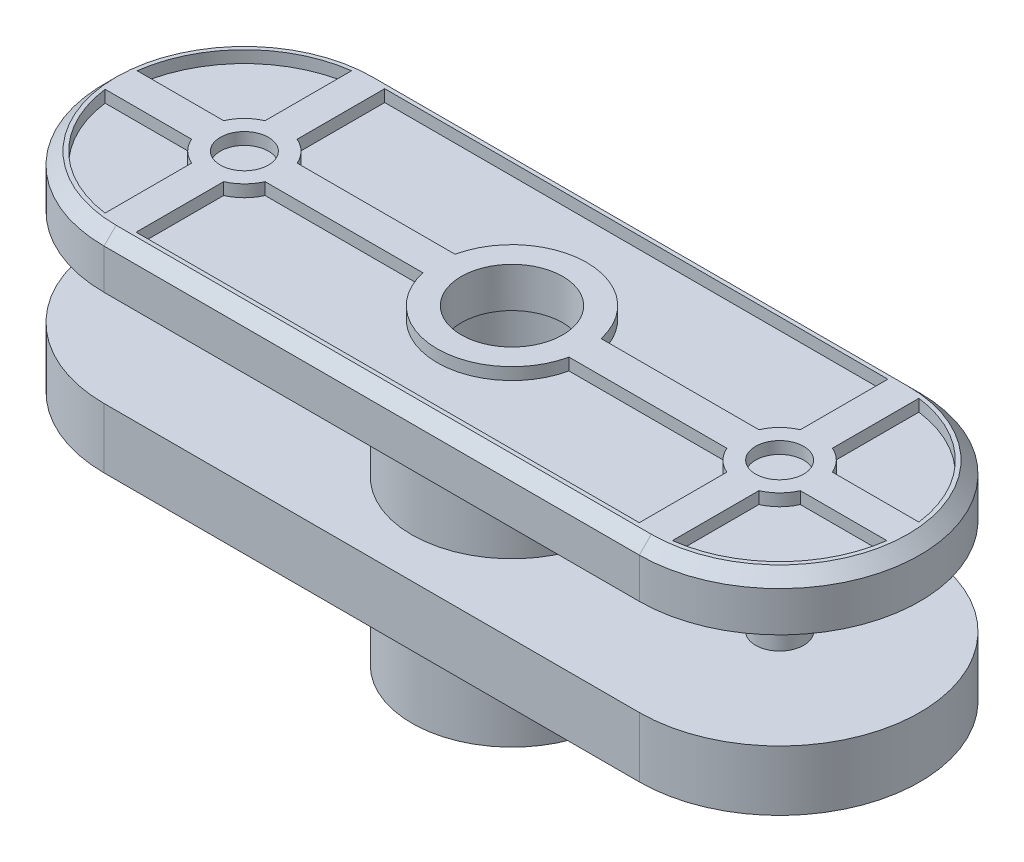
SolidWorks part; units mm, degrees
other "Marca1"
sketch "Croquis13" plane through (-10.175, 1.3, 3.5) normal (-0.1147, 0.8276, 0.5494) x (0.861, 0.3586, -0.3605)
ref_plane "Alzado" through (0, 0, 0) normal (0, 0, 1) x (1, 0, 0)
ref_plane "Planta" through (0, 0, 0) normal (0, 1, 0) x (1, 0, 0)
ref_plane "Vista lateral" through (0, 0, 0) normal (1, 0, 0) x (0, 0, -1)
sketch "Croquis1" plane through (0, 0, 0) normal (0, 1, 0) x (1, 0, 0)
  line L0 (-6.675, 0) -> (6.675, 0) construction
  line L1 (-6.675, 3.5) -> (6.675, 3.5)
  line L2 (6.675, -3.5) -> (-6.675, -3.5)
  line L3 (0, 6.0842) -> (0, -6.0842) construction
  arc A0 (6.675, 3.5) -> (6.675, -3.5) centre (6.675, 0) cw
  arc A1 (-6.675, 3.5) -> (-6.675, -3.5) centre (-6.675, 0) ccw
  point P0 (-10.175, 0)
  point P3 (0, -3.5)
  point P4 (0, 0)
  point P10 (0, 3.5)
  point P11 (10.175, 0)
  point P18 (0, 0)
  dimension "D1" = 20.35
  dimension "D2" = 7
extrude "Saliente-Extruir1" add sketch "Croquis1" along normal blind 1.3
sketch "Croquis2" plane through (0, 1.3, 0) normal (0, 1, 0) x (1, 0, 0)
  line L0 (-6.675, 3.5) -> (-6.675, -3.5) construction
  line L1 (-6.675, 0) -> (-10.175, 0) construction
  line L2 (-7.075, 3.0741) -> (-7.075, 0.9165)
  line L4 (-6.275, 3.1) -> (-6.275, 0.9165)
  line L6 (6.675, -3.5) -> (-6.675, -3.5) construction
  line L7 (-6.675, 3.5) -> (6.675, 3.5) construction
  line L8 (6.675, -3.5) -> (-6.675, -3.5)
  line L9 (-6.675, 3.5) -> (6.675, 3.5)
  line L10 (-7.075, 3.5) -> (-7.075, -3.5) construction
  line L11 (-6.275, -0.9165) -> (-6.275, -3.1)
  line L12 (-6.275, 3.5) -> (-6.275, -3.5) construction
  line L15 (-7.5915, -0.4) -> (-9.7491, -0.4)
  line L16 (-7.5915, 0.4) -> (-9.7491, 0.4)
  line L18 (-7.075, -0.9165) -> (-7.075, -3.0741)
  line L20 (-6.675, 0) -> (6.675, 0) construction
  line L21 (-6.675, 0) -> (6.675, 0) construction
  line L22 (0, 6.0842) -> (0, -6.0842) construction
  line L23 (-5.7585, 0.4) -> (5.7585, 0.4)
  line L24 (0, 0.4) -> (0, 0)
  line L25 (0, 6.0842) -> (0, -6.0842) construction
  line L26 (-6.675, 0.4) -> (6.675, 0.4) construction
  line L27 (6.275, -0.9165) -> (6.275, -3.1)
  line L28 (-5.7585, -0.4) -> (5.7585, -0.4)
  line L29 (7.075, -0.9165) -> (7.075, -3.0741)
  line L30 (7.5915, -0.4) -> (9.7491, -0.4)
  line L31 (7.5915, 0.4) -> (9.7491, 0.4)
  line L32 (7.075, 3.0741) -> (7.075, 0.9165)
  line L33 (6.275, 3.1) -> (6.275, 0.9165)
  line L34 (-6.275, 3.1) -> (6.275, 3.1)
  line L35 (6.275, -3.1) -> (-6.275, -3.1)
  line L36 (-6.675, 3.1) -> (6.675, 3.1) construction
  line L37 (6.675, -3.1) -> (-6.675, -3.1) construction
  arc A0 (-7.075, 0.9165) -> (-7.5915, 0.4) centre (-6.675, 0) ccw
  circle A1 centre (-6.675, 0) radius 0.6
  arc A2 (-6.675, 3.5) -> (-6.675, -3.5) centre (-6.675, 0) ccw construction
  arc A3 (6.675, -3.5) -> (6.675, 3.5) centre (6.675, 0) ccw construction
  arc A4 (6.675, -3.5) -> (6.675, 3.5) centre (6.675, 0) ccw
  arc A5 (-6.675, 3.5) -> (-6.675, -3.5) centre (-6.675, 0) ccw
  arc A6 (-7.5915, -0.4) -> (-7.075, -0.9165) centre (-6.675, 0) ccw
  arc A7 (-6.275, -0.9165) -> (-5.7585, -0.4) centre (-6.675, 0) ccw
  arc A8 (-5.7585, 0.4) -> (-6.275, 0.9165) centre (-6.675, 0) ccw
  arc A9 (6.275, -0.9165) -> (5.7585, -0.4) centre (6.675, 0) cw
  arc A10 (7.5915, -0.4) -> (7.075, -0.9165) centre (6.675, 0) cw
  arc A11 (7.075, 0.9165) -> (7.5915, 0.4) centre (6.675, 0) cw
  arc A12 (5.7585, 0.4) -> (6.275, 0.9165) centre (6.675, 0) cw
  circle A13 centre (6.675, 0) radius 0.6
  arc A14 (7.075, -3.0741) -> (9.7491, -0.4) centre (6.675, 0) ccw
  arc A15 (-7.075, 3.0741) -> (-9.7491, 0.4) centre (-6.675, 0) ccw
  arc A16 (-6.675, 3.1) -> (-6.675, -3.1) centre (-6.675, 0) ccw construction
  arc A17 (-9.7491, -0.4) -> (-7.075, -3.0741) centre (-6.675, 0) ccw
  arc A18 (9.7491, 0.4) -> (7.075, 3.0741) centre (6.675, 0) ccw
  arc A19 (6.675, -3.1) -> (6.675, 3.1) centre (6.675, 0) ccw construction
  point P42 (0, -0.4)
  dimension "D1" = 2
  dimension "D2" = 1.2
  dimension "D3" = 0.4
  dimension "D7" = 0.4
  dimension "D5" = 0.4
  dimension "D8" = 0.8
  dimension "D9" = 0.8
  dimension "D10" = 0.8
  dimension "D11" = 0.8
  dimension "D12" = 0.8
  dimension "D13" = 0.4
  dimension "D4" = 0.4
  dimension "D6" = 0.4
extrude "Cortar-Extruir1" cut sketch "Croquis2" against normal blind 0.3 contours L4 A8 L23 A12 L33 L34 | L27 L35 L11 A7 L28 A9 | A1 | L16 A15 L2 A0 | L18 A17 L15 A6 | L31 A18 L32 A11 | L29 A14 L30 A10 | A13
chamfer "Chaflán1" distance 0.3 angle 45 4 edges at (10.175, 1.3, 0) (0, 1.3, -3.5) (-10.175, 1.3, 0) (0, 1.3, 3.5)
ref_plane "Plano2" through (0, -1.2, 0) normal (0, 1, 0) x (1, 0, 0)
sketch "Croquis3" plane through (0, -1.2, 0) normal (0, 1, 0) x (1, 0, 0)
  circle A0 centre (6.675, 0) radius 0.6 construction
  circle A1 centre (-6.675, 0) radius 0.6 construction
  circle A2 centre (6.675, 0) radius 0.6
  circle A3 centre (-6.675, 0) radius 0.6
  circle A4 centre (0, 0) radius 2.5
  dimension "D1" = 5
extrude "Saliente-Extruir2" add sketch "Croquis3" along normal up to next
sketch "Croquis4" plane through (0, -1.2, 0) normal (0, 1, 0) x (1, 0, 0)
  circle A0 centre (6.675, 0) radius 0.6 construction
  circle A1 centre (-6.675, 0) radius 0.6 construction
  circle A2 centre (0, 0) radius 2.5 construction
  circle A3 centre (6.675, 0) radius 0.6
  circle A4 centre (-6.675, 0) radius 0.6
  circle A5 centre (0, 0) radius 2.5
extrude "Saliente-Extruir3" add sketch "Croquis4" against normal blind 1.2
sketch "Croquis5" plane through (0, -2.4, 0) normal (0, -1, 0) x (1, 0, 0)
  line L0 (6.675, -3.5) -> (-6.675, -3.5) construction
  line L1 (-6.675, 3.5) -> (6.675, 3.5) construction
  line L2 (6.675, -3.5) -> (-6.675, -3.5)
  line L3 (-6.675, 3.5) -> (6.675, 3.5)
  arc A0 (6.675, -3.5) -> (6.675, 3.5) centre (6.675, 0) ccw construction
  arc A1 (-6.675, 3.5) -> (-6.675, -3.5) centre (-6.675, 0) ccw construction
  arc A2 (6.675, -3.5) -> (6.675, 3.5) centre (6.675, 0) ccw
  arc A3 (-6.675, 3.5) -> (-6.675, -3.5) centre (-6.675, 0) ccw
extrude "Saliente-Extruir4" add sketch "Croquis5" along normal blind 1.5
sketch "Croquis6" plane through (0, -3.9, 0) normal (0, -1, 0) x (1, 0, 0)
  line L0 (-10.175, 0) -> (10.175, 0) construction
  line L1 (6.255, 3.08) -> (-6.255, 3.08)
  line L2 (0, 3.5) -> (0, -3.5) construction
  line L3 (-6.675, -3.5) -> (6.675, -3.5) construction
  line L4 (6.675, 3.5) -> (-6.675, 3.5) construction
  line L5 (-6.675, -3.5) -> (-6.675, 3.5) construction
  line L6 (6.675, -3.5) -> (6.675, 3.5) construction
  line L7 (-9.7262, -0.42) -> (-7.095, -0.42)
  line L8 (-6.255, -3.08) -> (-6.255, -0.42)
  line L9 (7.095, -3.0512) -> (7.095, -0.42)
  line L10 (-9.7262, 0.42) -> (-7.095, 0.42)
  line L11 (-7.095, -3.0512) -> (-7.095, -0.42)
  line L12 (6.255, -3.08) -> (6.255, -0.42)
  line L13 (-7.095, -3.5) -> (-7.095, 3.5) construction
  line L14 (-6.675, -3.5) -> (6.675, -3.5)
  line L15 (6.675, 3.5) -> (-6.675, 3.5)
  line L16 (-10.175, 0.42) -> (10.175, 0.42) construction
  line L17 (-10.175, -0.42) -> (10.175, -0.42) construction
  line L18 (7.095, -3.5) -> (7.095, 3.5) construction
  line L19 (-6.255, -3.08) -> (6.255, -3.08)
  line L20 (-6.255, -3.5) -> (-6.255, 3.5) construction
  line L21 (6.675, 3.08) -> (-6.675, 3.08) construction
  line L22 (-6.255, 0.42) -> (6.255, 0.42)
  line L23 (-6.255, -0.42) -> (6.255, -0.42)
  line L24 (-6.675, -3.08) -> (6.675, -3.08) construction
  line L25 (-6.255, 0.42) -> (-6.255, 3.08)
  line L26 (6.255, -3.5) -> (6.255, 3.5) construction
  line L27 (7.095, 0.42) -> (9.7262, 0.42)
  line L28 (7.095, -0.42) -> (9.7262, -0.42)
  line L29 (6.255, 0.42) -> (6.255, 3.08)
  line L30 (7.095, 0.42) -> (7.095, 3.0512)
  line L31 (-7.095, 0.42) -> (-7.095, 3.0512)
  arc A0 (6.675, -3.5) -> (6.675, 3.5) centre (6.675, 0) ccw construction
  arc A1 (-6.675, 3.5) -> (-6.675, -3.5) centre (-6.675, 0) ccw construction
  arc A2 (6.675, -3.5) -> (6.675, 3.5) centre (6.675, 0) ccw
  arc A3 (-6.675, 3.5) -> (-6.675, -3.5) centre (-6.675, 0) ccw
  arc A4 (-7.095, 3.0512) -> (-9.7262, 0.42) centre (-6.675, 0) ccw
  arc A5 (7.095, -3.0512) -> (9.7262, -0.42) centre (6.675, 0) ccw
  arc A6 (-6.675, 3.08) -> (-6.675, -3.08) centre (-6.675, 0) ccw construction
  arc A7 (-9.7262, -0.42) -> (-7.095, -3.0512) centre (-6.675, 0) ccw
  arc A8 (6.675, -3.08) -> (6.675, 3.08) centre (6.675, 0) ccw construction
  arc A9 (9.7262, 0.42) -> (7.095, 3.0512) centre (6.675, 0) ccw
  point P7 (0, 0)
  point P14 (0, 0)
  point P19 (-6.675, 0)
  dimension "D1" = 0.42
  dimension "D2" = 0.42
  dimension "D3" = 0.42
extrude "Cortar-Extruir3" cut sketch "Croquis6" against normal blind 0.75 contours L1 L25 L22 L29 | A4 L10 L31 | L11 L7 A7 | L12 L23 L8 L19 | L9 L28 A5 | A9 L30 L27
sketch "Croquis7" plane through (0, -3.9, 0) normal (0, -1, 0) x (1, 0, 0)
  line L2 (6.675, 3.5) -> (-6.675, 3.5)
  line L3 (-6.675, -3.5) -> (6.675, -3.5)
  line L4 (6.675, 3.5) -> (-6.675, 3.5)
  line L5 (-6.675, -3.5) -> (6.675, -3.5)
  arc A2 (6.675, -3.5) -> (6.675, 3.5) centre (6.675, 0) ccw
  arc A3 (-6.675, 3.5) -> (-6.675, -3.5) centre (-6.675, 0) ccw
  arc A4 (6.675, -3.5) -> (6.675, 3.5) centre (6.675, 0) ccw
  arc A5 (-6.675, 3.5) -> (-6.675, -3.5) centre (-6.675, 0) ccw
  dimension "D1" = 0
sketch "Croquis8" plane through (0, -3.15, 0) normal (0, -1, 0) x (1, 0, 0)
  circle A0 centre (0, 0) radius 2.5 construction
  circle A1 centre (0, 0) radius 2.5
extrude "Saliente-Extruir5" add sketch "Croquis8" along normal blind 3.32
sketch "Croquis9" plane through (0, -6.47, 0) normal (0, -1, 0) x (1, 0, 0)
  circle A0 centre (0, 0) radius 1.65
  arc A1 (2.4645, 0.42) -> (-2.4645, 0.42) centre (0, 0) ccw construction
  dimension "D1" = 0.85
extrude "Cortar-Extruir4" cut sketch "Croquis9" against normal blind 6.77
sketch "Croquis10" plane through (0, 0.3, 0) normal (0, -1, 0) x (1, 0, 0)
  circle A0 centre (0, 0) radius 1.265
  dimension "D1" = 2.53
extrude "Cortar-Extruir6" cut sketch "Croquis10" against normal blind 6.77
sketch "Croquis12" plane through (0, 1, 0) normal (0, 1, 0) x (1, 0, 0)
  circle A0 centre (0, 0) radius 1.265 construction
  circle A1 centre (0, 0) radius 1.265
  circle A2 centre (0, 0) radius 1.865
  dimension "D1" = 0.6
extrude "Saliente-Extruir6" add sketch "Croquis12" along normal up to surface (0.3 mm away) up to face at (0, 1.3, 0)
